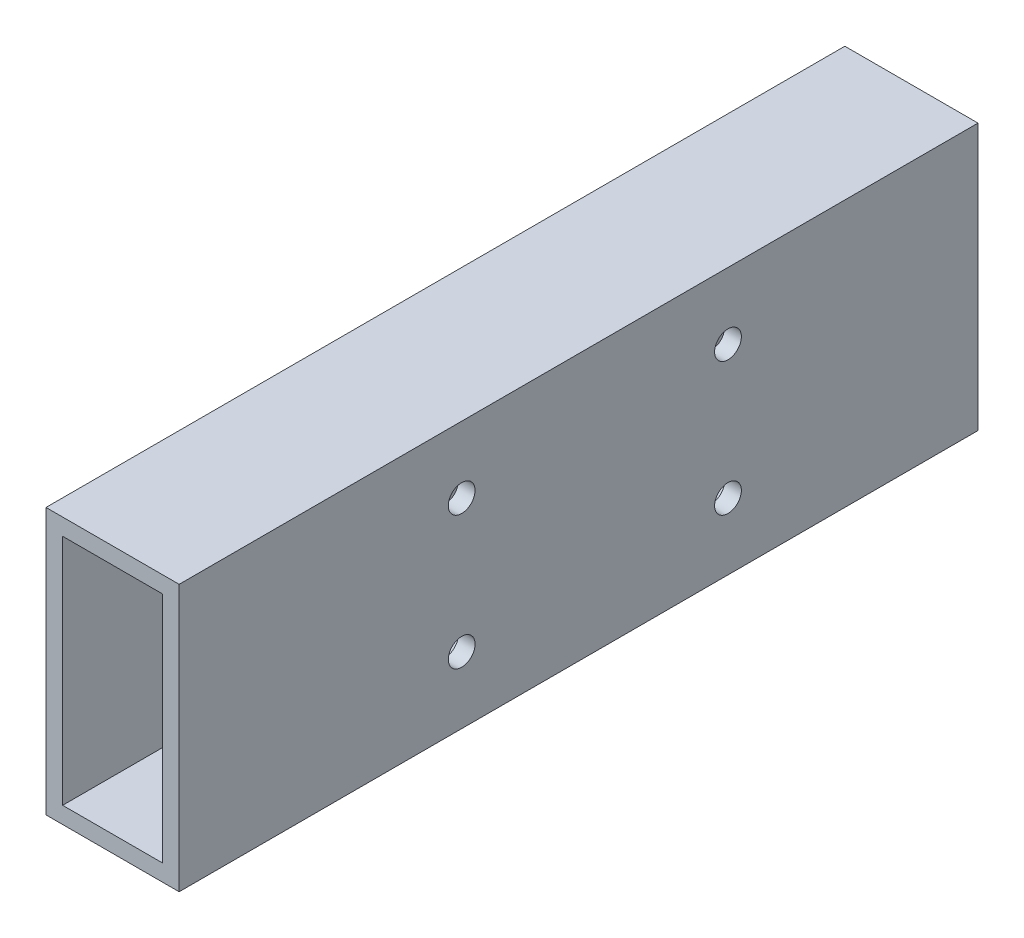
SolidWorks part; units mm, degrees
ref_plane "Front Plane" through (0, 0, 0) normal (0, 0, 1) x (1, 0, 0)
ref_plane "Top Plane" through (0, 0, 0) normal (0, 1, 0) x (1, 0, 0)
ref_plane "Right Plane" through (0, 0, 0) normal (1, 0, 0) x (0, 0, -1)
sketch "Sketch1" plane through (0, 0, 0) normal (0, 0, 1) x (1, 0, 0)
  line L0 (-9.525, 22.225) -> (9.525, 22.225)
  line L1 (-12.7, 25.4) -> (12.7, 25.4)
  line L2 (-12.7, 25.4) -> (-12.7, -25.4)
  line L3 (-12.7, -25.4) -> (12.7, -25.4)
  line L4 (12.7, 25.4) -> (12.7, -25.4)
  line L5 (-12.7, 25.4) -> (12.7, -25.4) construction
  line L6 (-12.7, -25.4) -> (12.7, 25.4) construction
  line L7 (9.525, 22.225) -> (9.525, -22.225)
  line L8 (-9.525, -22.225) -> (9.525, -22.225)
  line L9 (-9.525, 22.225) -> (-9.525, -22.225)
  point P0 (0, 0)
  dimension "D1" = 25.4
  dimension "D2" = 50.8
  dimension "D3" = 3.175
extrude "Boss-Extrude1" add sketch "Sketch1" along normal mid plane 152.4
hole_wizard "#10 Clearance Hole1" positions "Sketch3" profile "Sketch2" hole size "#10" standard "ANSI Inch" end condition through all
sketch "Sketch3" plane through (12.7, 0, 0) normal (1, 0, 0) x (0, 0, -1)
  line L0 (-22.2988, -12.7) -> (-22.2988, 12.7) construction
  point P0 (-22.2988, 12.7)
  point P7 (28.5012, 12.7)
  point P8 (28.5012, -12.7)
  point P9 (-22.2988, -12.7)
  point P13 (-22.2988, 0)
  dimension "D1" = 2
  dimension "D2" = 2
sketch "Sketch2" plane through (12.7, 12.7, 22.2988) normal (0, 1, 0) x (0, 0, -1)
  line L0 (0, 0) -> (0, 25.4)
  line L1 (0, 25.4) -> (2.5527, 25.4)
  line L2 (2.5527, 25.4) -> (2.5527, 0)
  line L5 (2.5527, 0) -> (0, 0)
  line L11 (0, -6.35) -> (0, 107.95) construction
  dimension "Thru Hole Dia." = 5.1054
  dimension "Thru Hole Depth" = 25.4
